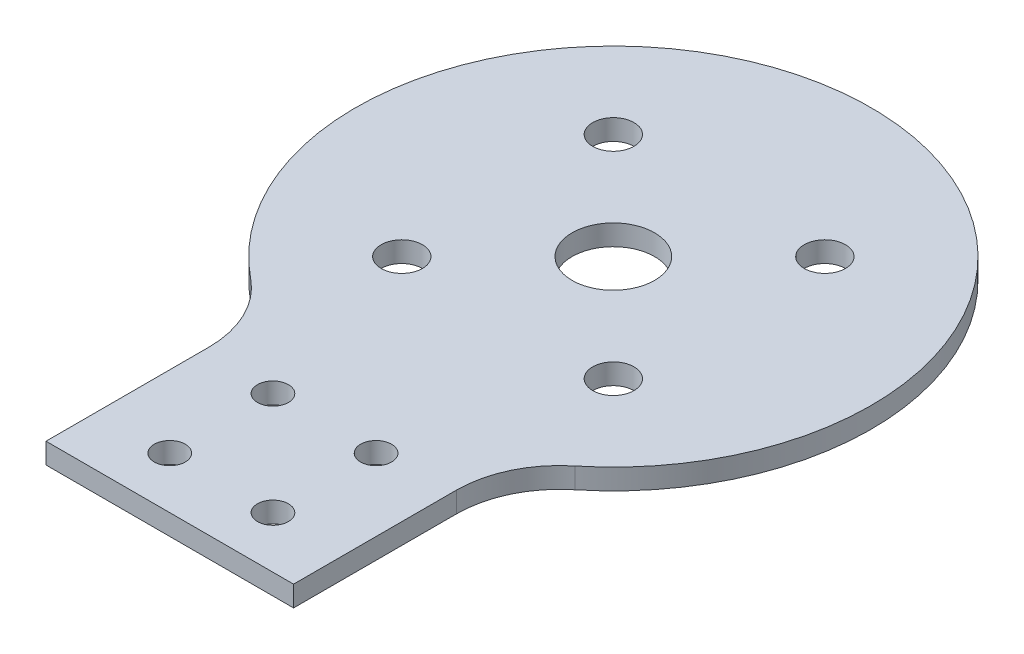
SolidWorks part; units mm, degrees
ref_plane "前视基准面" through (0, 0, 0) normal (0, 0, 1) x (1, 0, 0)
ref_plane "上视基准面" through (0, 0, 0) normal (0, 1, 0) x (1, 0, 0)
ref_plane "右视基准面" through (0, 0, 0) normal (1, 0, 0) x (0, 0, -1)
other "Configuration Table"
sketch "草图2" plane through (0, 0, 0) normal (0, 1, 0) x (1, 0, 0)
  line L5 (-23, -23) -> (23, 23) construction
  line L6 (-23, 23) -> (23, -23) construction
  circle A0 centre (0, 0) radius 6
  circle A1 centre (0, 0) radius 4
extrude "凸台-拉伸1" add sketch "草图2" along normal blind 2
sketch "草图4" plane through (0, 2, 0) normal (0, 1, 0) x (1, 0, 0)
  line L5 (-10.253, 10.253) -> (10.253, -10.253) construction
  line L6 (-10.253, -10.253) -> (10.253, 10.253) construction
  line L11 (-39, 39) -> (39, -39) construction
  line L12 (-39, -39) -> (39, 39) construction
  circle A0 centre (0, 0) radius 5
  circle A1 centre (-10.253, 10.253) radius 2
  circle A2 centre (10.253, 10.253) radius 2
  circle A3 centre (-10.253, -10.253) radius 2
  circle A4 centre (10.253, -10.253) radius 2
  circle A5 centre (0, 0) radius 25
  point P0 (0, 0)
  point P7 (0, 0)
  point P17 (0, 0)
extrude "凸台-拉伸3" add sketch "草图4" against normal blind 2
sketch "草图3" plane through (0, 2, 0) normal (0, 1, 0) x (1, 0, 0)
  line L4 (-12, -43) -> (12, -43)
  line L5 (12, -43) -> (12, -21.9317)
  line L6 (12, -21.9317) -> (-12, -21.9317)
  line L7 (-12, -21.9317) -> (-12, -43)
  circle A6 centre (0, 0) radius 25 construction
  point P9 (0, -38)
  point P11 (0, -43)
extrude "凸台-拉伸2" add sketch "草图3" against normal blind 2
sketch "草图5" plane through (0, 2, 0) normal (0, 1, 0) x (1, 0, 0)
  circle A0 centre (5, -28) radius 1.5
  circle A1 centre (5, -38) radius 1.5
  circle A2 centre (-5, -28) radius 1.5
  circle A3 centre (-5, -38) radius 1.5
extrude "切除-拉伸1" cut sketch "草图5" against normal through all
fillet "圆角1" radius 10 2 edges at (12, 1, 21.9317) (-12, 1, 21.9317)
